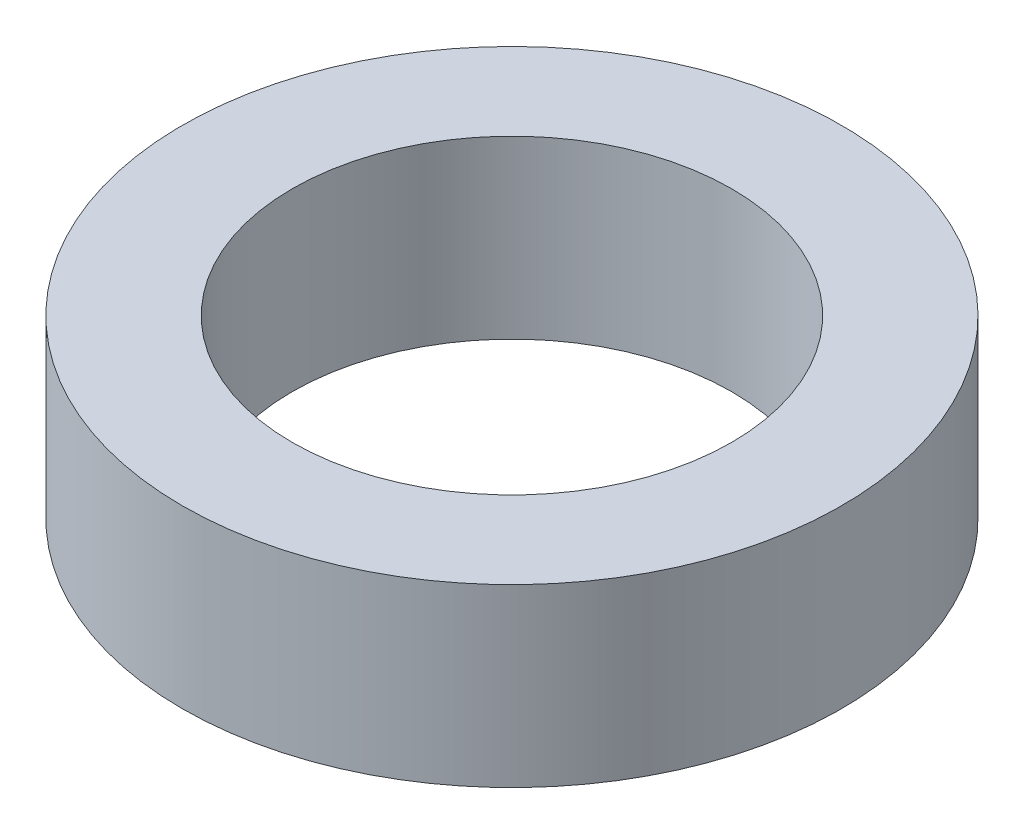
SolidWorks part; units mm, degrees
ref_plane "Ön Düzlem" through (0, 0, 0) normal (0, 0, 1) x (1, 0, 0)
ref_plane "Üst Düzlem" through (0, 0, 0) normal (0, 1, 0) x (1, 0, 0)
ref_plane "Sağ Düzlem" through (0, 0, 0) normal (1, 0, 0) x (0, 0, -1)
sketch "Sketch1" plane through (0, 0, 0) normal (0, 1, 0) x (1, 0, 0)
  circle A0 centre (0, 0) radius 5
  circle A1 centre (0, 0) radius 7.5
  dimension "D1" = 10
  dimension "D2" = 15
extrude "Boss-Extrude1" add sketch "Sketch1" along normal blind 4
